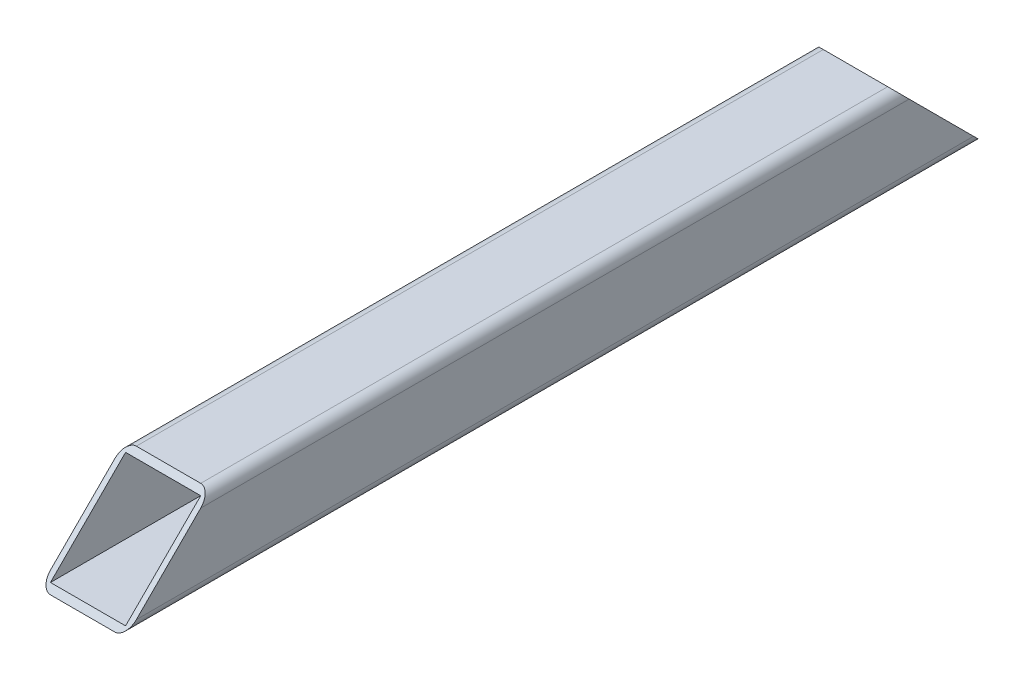
SolidWorks part; units mm, degrees
material "6063-O"
ref_plane "Front Plane" through (0, 0, 0) normal (0, 0, 1) x (1, 0, 0)
ref_plane "Top Plane" through (0, 0, 0) normal (0, 1, 0) x (1, 0, 0)
ref_plane "Right Plane" through (0, 0, 0) normal (1, 0, 0) x (0, 0, -1)
sketch "Sketch1" plane through (0, 0, 0) normal (0, 0, 1) x (1, 0, 0)
  line L1 (25.4, -25.4) -> (-25.4, -25.4)
  line L2 (25.4, -25.4) -> (25.4, 25.4)
  line L3 (25.4, 25.4) -> (-25.4, 25.4)
  line L4 (-25.4, -25.4) -> (-25.4, 25.4)
  line L5 (25.4, -25.4) -> (-25.4, 25.4) construction
  line L6 (25.4, 25.4) -> (-25.4, -25.4) construction
  line L7 (22.225, -22.225) -> (-22.225, -22.225)
  line L8 (22.225, -22.225) -> (22.225, 22.225)
  line L9 (22.225, 22.225) -> (-22.225, 22.225)
  line L10 (-22.225, -22.225) -> (-22.225, 22.225)
  line L11 (22.225, -22.225) -> (-22.225, 22.225) construction
  line L12 (22.225, 22.225) -> (-22.225, -22.225) construction
  point P0 (0, 0)
  point P6 (0, 0)
  dimension "D1" = 50.8
  dimension "D2" = 50.8
  dimension "D3" = 3.175
  dimension "D4" = 3.175
extrude "Boss-Extrude1" add sketch "Sketch1" along normal mid plane 508
fillet "Fillet1" radius 6.35 4 edges at (25.4, -25.4, 0) (-25.4, -25.4, 0) (-25.4, 25.4, 0) (25.4, 25.4, 0)
sketch "Sketch2" plane through (-25.4, 0, 0) normal (-1, 0, 0) x (0, 0, 1)
  line L0 (254, -25.4) -> (203.2, 25.4)
  line L1 (-254, 25.4) -> (254, 25.4) construction
  line L2 (254, 19.05) -> (254, -19.05) construction
  line L3 (203.2, 25.4) -> (254, 25.4)
  line L4 (254, 25.4) -> (254, -25.4)
  line L6 (0, -1000) -> (0, 49000) construction
  line L7 (-254, 25.4) -> (-254, -25.4)
  line L8 (-203.2, 25.4) -> (-254, 25.4)
  line L9 (-254, -25.4) -> (-203.2, 25.4)
  dimension "D1" = 45
extrude "Cut-Extrude1" cut sketch "Sketch2" against normal blind 914.4
hole_wizard "1/4 Clearance Hole2" positions "Sketch3" profile "Sketch4" hole size "1/4" standard "ANSI Inch"
sketch "Sketch3" plane through (25.4, 0, 0) normal (1, 0, 0) x (0, 0, -1)
  line L0 (0, -1000) -> (0, 49000) construction
  line L1 (-1000, 0) -> (49000, 0) construction
  point P50 (-30.099, -6.096)
  point P55 (30.099, 6.096)
  point P63 (-15.875, 6.096)
  point P65 (15.875, -6.096)
  dimension "D1" = 6.096
  dimension "D2" = 6.096
  dimension "D3" = 15.875
  dimension "D4" = 15.875
  dimension "D5" = 30.099
  dimension "D6" = 30.099
  dimension "D7" = 6.096
  dimension "D8" = 6.096
sketch "Sketch4" plane through (25.4, -6.096, 30.099) normal (0, 1, 0) x (0, 0, -1)
  line L0 (0, 0) -> (0, 50.8)
  line L1 (0, 50.8) -> (3.3782, 50.8)
  line L2 (3.3782, 50.8) -> (3.3782, 0)
  line L5 (3.3782, 0) -> (0, 0)
  line L11 (0, -6.35) -> (0, 107.95) construction
  dimension "Thru Hole Dia." = 6.7564
  dimension "Thru Hole Depth" = 50.8
hole_wizard "1/4 Clearance Hole3" positions "Sketch5" profile "Sketch6" hole size "1/4" standard "ANSI Inch"
sketch "Sketch5" plane through (0, 25.4, 0) normal (0, 1, 0) x (1, 0, 0)
  line L0 (0, -1000) -> (0, 49000) construction
  line L1 (-1000, 0) -> (49000, 0) construction
  point P0 (6.35, 38.1)
  point P2 (6.35, -28.575)
  point P4 (-6.35, 28.575)
  point P6 (-6.35, -38.1)
  dimension "D1" = 38.1
  dimension "D2" = 28.575
  dimension "D3" = 28.575
  dimension "D4" = 38.1
  dimension "D5" = 6.35
  dimension "D6" = 6.35
sketch "Sketch6" plane through (6.35, 25.4, -38.1) normal (1, 0, 0) x (0, 0, 1)
  line L0 (0, 0) -> (0, 50.8)
  line L1 (0, 50.8) -> (3.3782, 50.8)
  line L2 (3.3782, 50.8) -> (3.3782, 0)
  line L5 (3.3782, 0) -> (0, 0)
  line L11 (0, -6.35) -> (0, 107.95) construction
  dimension "Thru Hole Dia." = 6.7564
  dimension "Thru Hole Depth" = 50.8
